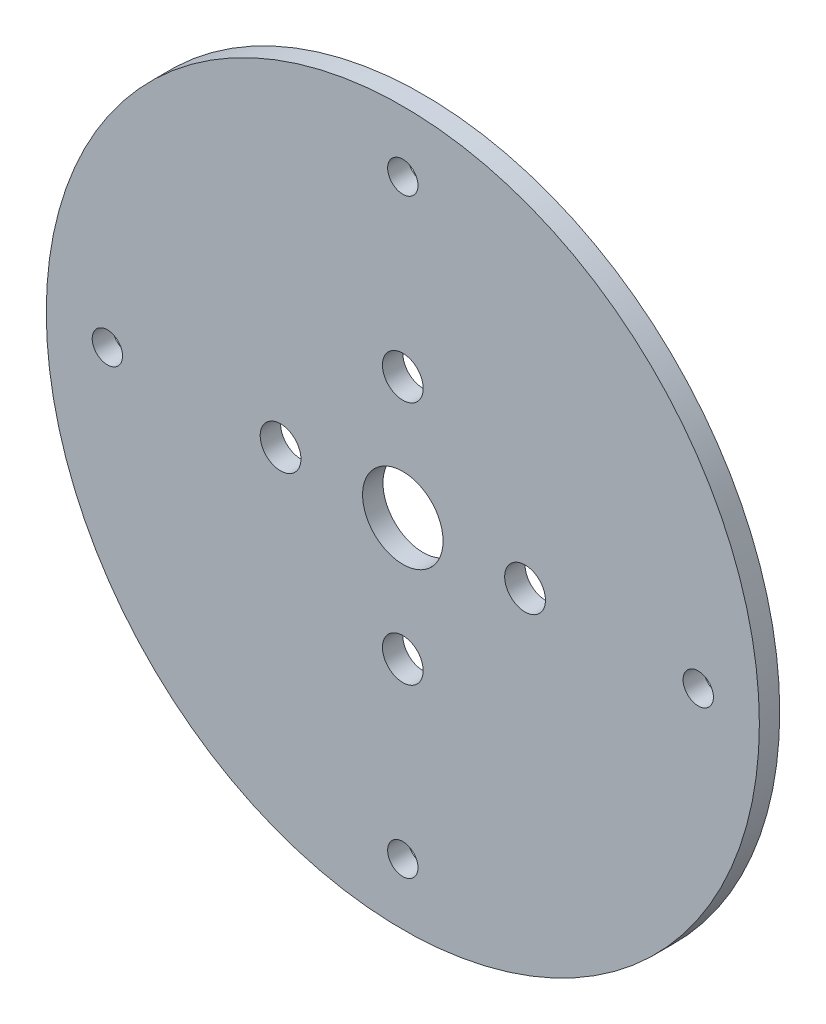
SolidWorks part; units mm, degrees
ref_plane "Front Plane" through (0, 0, 0) normal (0, 0, 1) x (1, 0, 0)
ref_plane "Top Plane" through (0, 0, 0) normal (0, 1, 0) x (1, 0, 0)
ref_plane "Right Plane" through (0, 0, 0) normal (1, 0, 0) x (0, 0, -1)
sketch "Sketch1" plane through (0, 0, 0) normal (0, 0, 1) x (1, 0, 0)
  line L0 (0, 0) -> (-29, 0) construction
  line L1 (0, 0) -> (29, 0) construction
  line L2 (0, 0) -> (0, 29) construction
  line L3 (0, 0) -> (0, -29) construction
  line L4 (0, 0) -> (12, 0) construction
  line L5 (0, 0) -> (0, 12) construction
  line L6 (0, 0) -> (-12, 0) construction
  line L7 (0, 0) -> (0, -12) construction
  circle A0 centre (0, 0) radius 35
  circle A1 centre (0, 0) radius 3.95
  circle A2 centre (-29, 0) radius 1.49
  circle A3 centre (29, 0) radius 1.49
  circle A4 centre (0, 29) radius 1.49
  circle A5 centre (0, -29) radius 1.49
  circle A6 centre (0, 12) radius 2
  circle A7 centre (12, 0) radius 2
  circle A8 centre (0, -12) radius 2
  circle A9 centre (-12, 0) radius 2
  dimension "D1" = 70
  dimension "D2" = 7.9
  dimension "D3" = 2.98
  dimension "D4" = 2.98
  dimension "D5" = 2.98
  dimension "D6" = 2.98
  dimension "D11" = 4
  dimension "D12" = 4
  dimension "D13" = 4
  dimension "D14" = 4
  dimension "D7" = 29
  dimension "D8" = 29
  dimension "D9" = 29
  dimension "D10" = 29
extrude "Boss-Extrude1" add sketch "Sketch1" along normal blind 2
